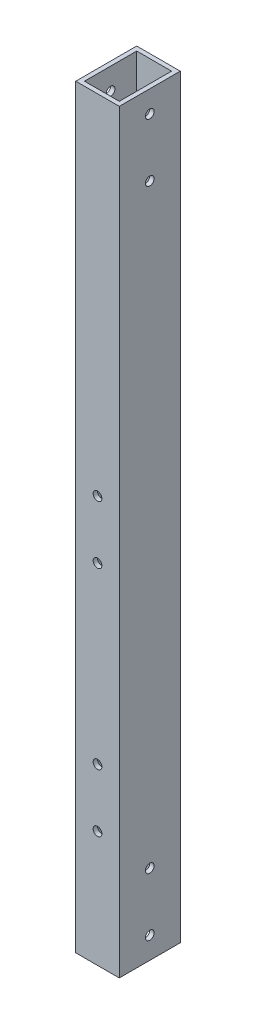
SolidWorks part; units mm, degrees
material "Thornel Mat VMA"
ref_plane "前视基准面" through (0, 0, 0) normal (0, 0, 1) x (1, 0, 0)
ref_plane "上视基准面" through (0, 0, 0) normal (0, 1, 0) x (1, 0, 0)
ref_plane "右视基准面" through (0, 0, 0) normal (1, 0, 0) x (0, 0, -1)
sketch "草图1" plane through (0, 0, 0) normal (0, 1, 0) x (1, 0, 0)
  line L1 (-7.5, -10.5) -> (7.5, -10.5)
  line L2 (-7.5, -10.5) -> (-7.5, 10.5)
  line L3 (-7.5, 10.5) -> (7.5, 10.5)
  line L4 (7.5, -10.5) -> (7.5, 10.5)
  line L5 (-7.5, -10.5) -> (7.5, 10.5) construction
  line L6 (-7.5, 10.5) -> (7.5, -10.5) construction
  point P0 (0, 0)
  dimension "D1" = 21
  dimension "D2" = 15
extrude "拉伸-薄壁1" add sketch "草图1" along normal blind 260 thin thin type one direction reverse wall 1.5
sketch "草图4" plane through (7.5, 0, 0) normal (1, 0, 0) x (0, 0, -1)
  line L0 (0, 0) -> (0, 260) construction
  line L1 (-10.5, 260) -> (10.5, 260) construction
  line L2 (-10.5, 0) -> (10.5, 0) construction
  circle A0 centre (0, 252.5) radius 1.5
  circle A1 centre (0, 232.5) radius 1.5
  circle A2 centre (0, 27.5) radius 1.5
  circle A3 centre (0, 7.5) radius 1.5
  dimension "D1" = 3
  dimension "D5" = 205
  dimension "D2" = 7.5
  dimension "D3" = 20
  dimension "D4" = 20
extrude "切除-拉伸2" cut sketch "草图4" against normal through all
sketch "草图5" plane through (0, 0, 10.5) normal (0, 0, 1) x (1, 0, 0)
  line L0 (0, 0) -> (0, 260) construction
  line L1 (-7.5, 260) -> (7.5, 260) construction
  line L2 (-7.5, 0) -> (7.5, 0) construction
  circle A0 centre (0, 40) radius 1.5
  circle A1 centre (0, 60) radius 1.5
  circle A2 centre (0, 120) radius 1.5
  circle A3 centre (0, 140) radius 1.5
  dimension "D1" = 3
  dimension "D2" = 20
  dimension "D3" = 20
  dimension "D4" = 60
  dimension "D5" = 40
extrude "切除-拉伸3" cut sketch "草图5" against normal through all
